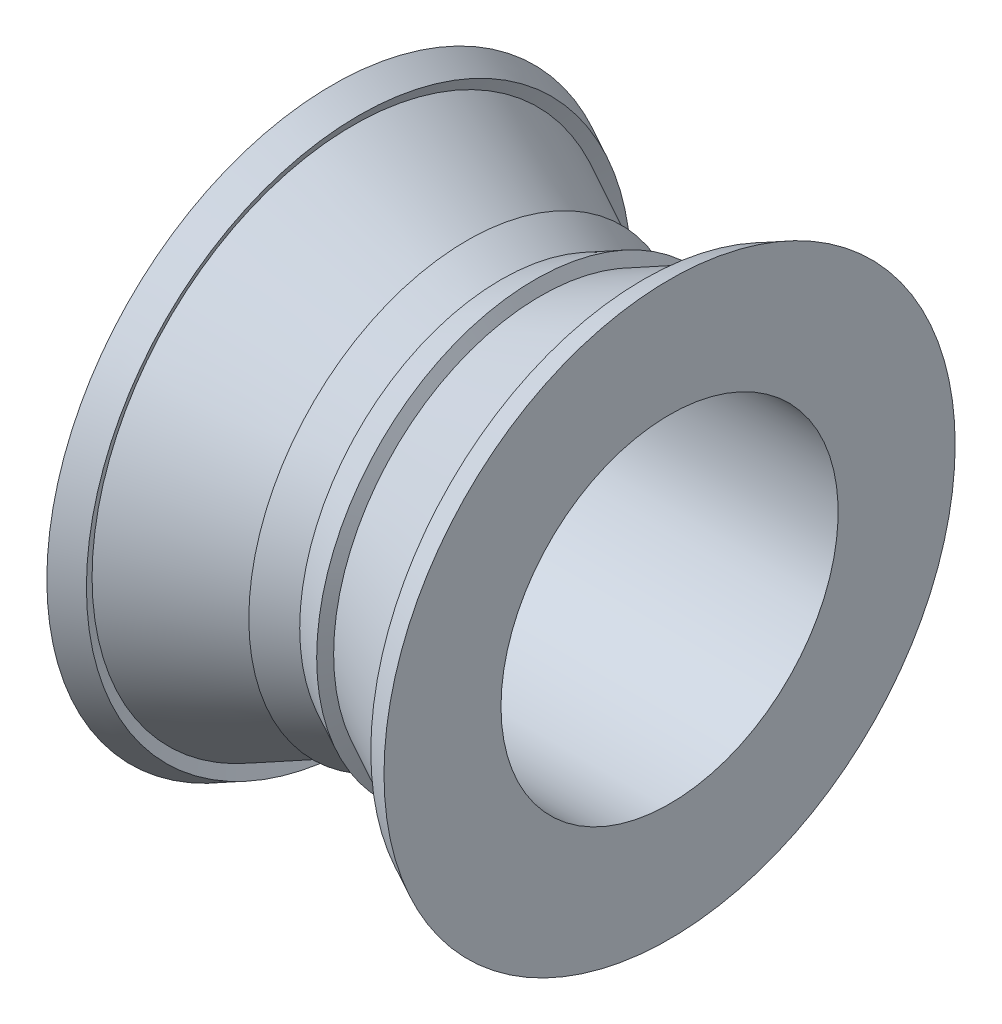
SolidWorks part; units mm, degrees
ref_plane "Front Plane" through (0, 0, 0) normal (0, 0, 1) x (1, 0, 0)
ref_plane "Top Plane" through (0, 0, 0) normal (0, 1, 0) x (1, 0, 0)
ref_plane "Right Plane" through (0, 0, 0) normal (1, 0, 0) x (0, 0, -1)
sketch "Sketch2" plane through (0, 0, 0) normal (0, 0, 1) x (1, 0, 0)
  line L1 (0, 40) -> (0, 26.118)
  line L2 (40, 40) -> (0, 40)
  line L3 (40, 40) -> (40, 26.118)
  line L4 (-8.8928, 60) -> (46.4098, 60) construction
  line L6 (24.0249, 34.1056) -> (24.6957, 35.4472)
  line L7 (24.0249, 34.1056) -> (20, 36.118)
  line L10 (36.8695, 27.6833) -> (40, 26.118)
  line L11 (37.5403, 29.0249) -> (36.8695, 27.6833)
  line L14 (2.4597, 29.0249) -> (3.1305, 27.6833)
  line L15 (3.1305, 27.6833) -> (0, 26.118)
  line L19 (15.3043, 35.4472) -> (2.4597, 29.0249)
  line L21 (24.6957, 35.4472) -> (37.5403, 29.0249)
  line L24 (15.9751, 34.1056) -> (15.3043, 35.4472)
  line L26 (15.9751, 34.1056) -> (20, 36.118)
  dimension "D2" = 40
  dimension "D3" = 20
revolve "Revolve1" add sketch "Sketch2" angle 360 about L4
